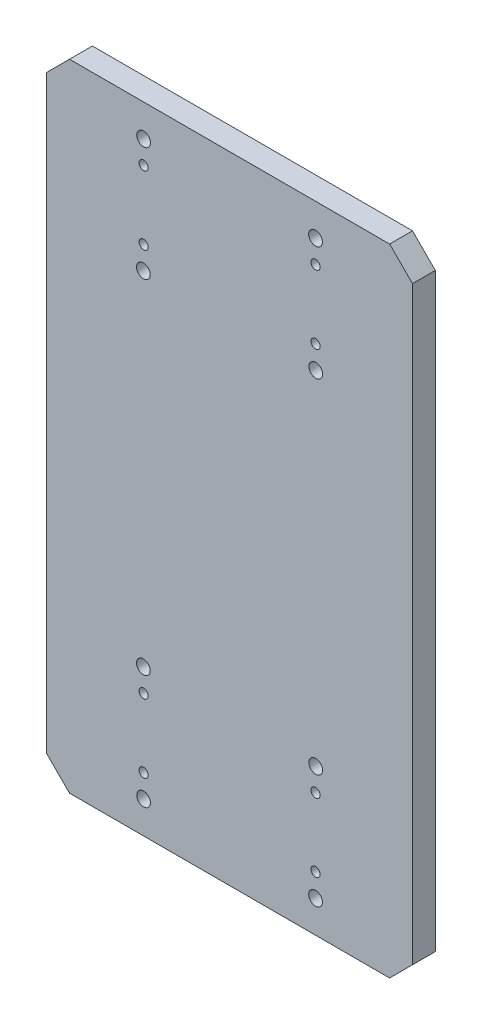
SolidWorks part; units mm, degrees
ref_plane "Front Plane" through (0, 0, 0) normal (0, 0, 1) x (1, 0, 0)
ref_plane "Top Plane" through (0, 0, 0) normal (0, 1, 0) x (1, 0, 0)
ref_plane "Right Plane" through (0, 0, 0) normal (1, 0, 0) x (0, 0, -1)
ref_plane "Plane1" through (0, 0, 5) normal (0, 0, 1) x (1, 0, 0)
sketch "Sketch1" plane through (0, 0, 5) normal (0, 0, 1) x (1, 0, 0)
  line L0 (-40, -69.5) -> (40, -69.5)
  line L1 (40, -69.5) -> (40, 69.5)
  line L2 (40, 69.5) -> (-40, 69.5)
  line L3 (-40, 69.5) -> (-40, -69.5)
extrude "Boss-Extrude1" add sketch "Sketch1" against normal blind 5
hole_wizard "Ø3.0 (3) Diameter Hole1" positions "Sketch3" profile "Sketch2" hole size "Ø3.0" standard "ANSI Metric"
sketch "Sketch3" plane through (0, 0, 0) normal (0, 0, -1) x (-1, 0, 0)
  point P0 (-18.8, 62.5)
  point P1 (18.8, -62.5)
  point P2 (-18.8455, -37.5)
  point P3 (18.8455, -37.5)
  point P4 (18.8, 62.5)
  point P5 (-18.8455, 37.5)
  point P6 (18.8455, 37.5)
  point P7 (-18.8, -62.5)
sketch "Sketch2" plane through (18.8, 62.5, 0) normal (1, 0, 0) x (0, 1, 0)
  line L0 (0, 0) -> (0, 5)
  line L1 (0, 5) -> (1.5, 5)
  line L2 (1.5, 5) -> (1.5, 0)
  line L5 (1.5, 0) -> (0, 0)
  line L11 (0, -6.35) -> (0, 107.95) construction
  dimension "Thru Hole Dia." = 3
  dimension "Thru Hole Depth" = 5
hole_wizard "Ø2.0 (2) Diameter Hole1" positions "Sketch5" profile "Sketch4" hole size "Ø2.0" standard "ANSI Metric"
sketch "Sketch5" plane through (0, 0, 0) normal (0, 0, -1) x (-1, 0, 0)
  point P0 (-18.8, 42.5)
  point P1 (-18.8, 57.5)
  point P2 (18.8, 42.5)
  point P3 (-18.8, -57.5)
  point P4 (-18.8, -42.5)
  point P5 (18.8, -57.5)
  point P6 (18.8, -42.5)
  point P7 (18.8, 57.5)
sketch "Sketch4" plane through (18.8, 42.5, 0) normal (1, 0, 0) x (0, 1, 0)
  line L0 (0, 0) -> (0, 5)
  line L1 (0, 5) -> (1, 5)
  line L2 (1, 5) -> (1, 0)
  line L5 (1, 0) -> (0, 0)
  line L11 (0, -6.35) -> (0, 107.95) construction
  dimension "Thru Hole Dia." = 2
  dimension "Thru Hole Depth" = 5
chamfer "Chamfer1" distance 1.5 angle 50 8 edges at (17.3, -62.5, 0) (-20.3, -62.5, 0) (-20.3455, 37.5, 0) (17.3455, -37.5, 0) (-20.3455, -37.5, 0) (-20.3, 62.5, 0) (17.3, 62.5, 0) (17.3455, 37.5, 0)
chamfer "Chamfer2" distance 5 angle 45 4 edges at (-40, 69.5, 2.5) (-40, -69.5, 2.5) (40, -69.5, 2.5) (40, 69.5, 2.5)
